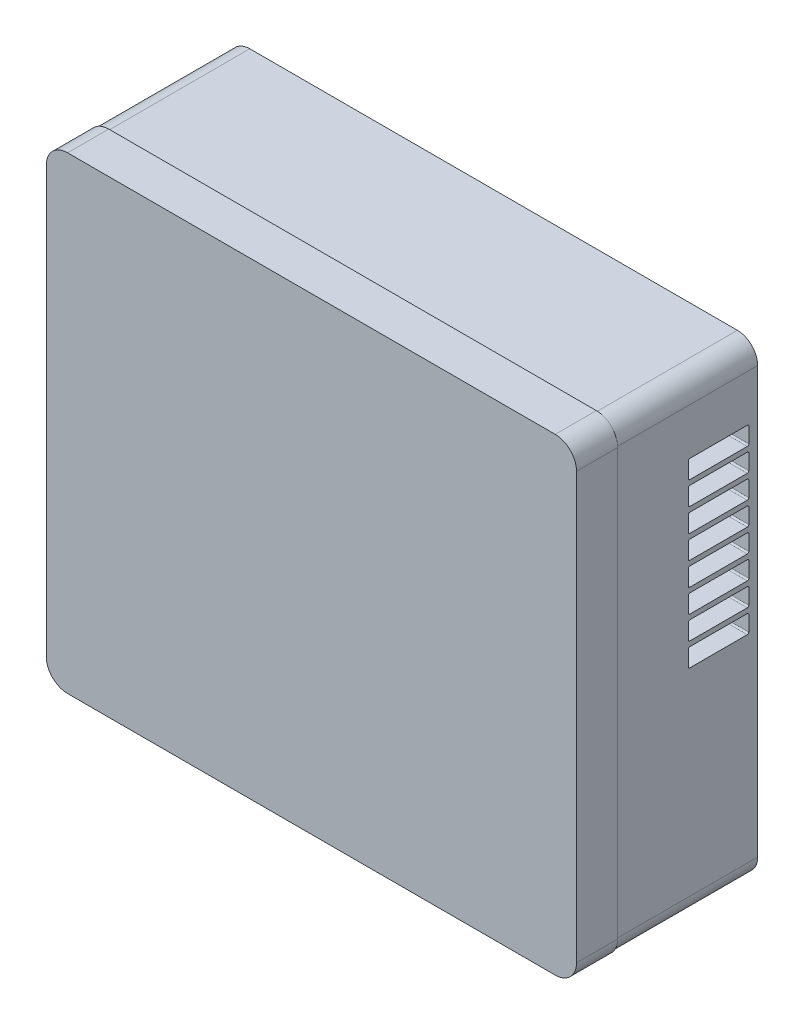
SolidWorks part; units mm, degrees
ref_plane "Front Plane" through (0, 0, 0) normal (0, 0, 1) x (1, 0, 0)
ref_plane "Top Plane" through (0, 0, 0) normal (0, 1, 0) x (1, 0, 0)
ref_plane "Right Plane" through (0, 0, 0) normal (1, 0, 0) x (0, 0, -1)
sketch "Sketch1" plane through (0, 0, 0) normal (0, 0, 1) x (1, 0, 0)
  line L4 (-86.3, 47.45) -> (-86.3, -38.45)
  line L5 (-84, -40.75) -> (14.4, -40.75)
  line L6 (16.7, -38.45) -> (16.7, 47.45)
  line L7 (14.4, 49.75) -> (-84, 49.75)
  line L8 (-86.3, 47.45) -> (-86.3, -38.45)
  line L9 (-84, -40.75) -> (14.4, -40.75)
  line L10 (16.7, -38.45) -> (16.7, 47.45)
  line L11 (14.4, 49.75) -> (-84, 49.75)
  arc A4 (-86.3, -38.45) -> (-84, -40.75) centre (-84, -38.45) ccw
  arc A5 (14.4, -40.75) -> (16.7, -38.45) centre (14.4, -38.45) ccw
  arc A6 (16.7, 47.45) -> (14.4, 49.75) centre (14.4, 47.45) ccw
  arc A7 (-84, 49.75) -> (-86.3, 47.45) centre (-84, 47.45) ccw
  arc A8 (-86.3, -38.45) -> (-84, -40.75) centre (-84, -38.45) ccw
  arc A9 (14.4, -40.75) -> (16.7, -38.45) centre (14.4, -38.45) ccw
  arc A10 (16.7, 47.45) -> (14.4, 49.75) centre (14.4, 47.45) ccw
  arc A11 (-84, 49.75) -> (-86.3, 47.45) centre (-84, 47.45) ccw
  dimension "D1" = 0
sketch "Sketch2" plane through (0, 0, 0) normal (0, 0, 1) x (1, 0, 0)
  line L4 (-86.3, 47.45) -> (-86.3, -38.45)
  line L5 (-84, -40.75) -> (14.4, -40.75)
  line L6 (16.7, -38.45) -> (16.7, 47.45)
  line L7 (14.4, 49.75) -> (-84, 49.75)
  line L8 (-86.3, 47.45) -> (-86.3, -38.45)
  line L9 (-84, -40.75) -> (14.4, -40.75)
  line L10 (16.7, -38.45) -> (16.7, 47.45)
  line L11 (14.4, 49.75) -> (-84, 49.75)
  arc A4 (-86.3, -38.45) -> (-84, -40.75) centre (-84, -38.45) ccw
  arc A5 (14.4, -40.75) -> (16.7, -38.45) centre (14.4, -38.45) ccw
  arc A6 (16.7, 47.45) -> (14.4, 49.75) centre (14.4, 47.45) ccw
  arc A7 (-84, 49.75) -> (-86.3, 47.45) centre (-84, 47.45) ccw
  arc A8 (-86.3, -38.45) -> (-84, -40.75) centre (-84, -38.45) ccw
  arc A9 (14.4, -40.75) -> (16.7, -38.45) centre (14.4, -38.45) ccw
  arc A10 (16.7, 47.45) -> (14.4, 49.75) centre (14.4, 47.45) ccw
  arc A11 (-84, 49.75) -> (-86.3, 47.45) centre (-84, 47.45) ccw
  dimension "D1" = 0
extrude "Boss-Extrude1" add sketch "Sketch2" along normal blind 2
sketch "Sketch3" plane through (0, 0, 2) normal (0, 0, 1) x (1, 0, 0)
  line L8 (-88.3, 47.45) -> (-88.3, -38.45)
  line L9 (-84, -42.75) -> (14.4, -42.75)
  line L10 (18.7, -38.45) -> (18.7, 47.45)
  line L11 (14.4, 51.75) -> (-84, 51.75)
  line L12 (-88.3, 47.45) -> (-88.3, -38.45)
  line L13 (-84, -42.75) -> (14.4, -42.75)
  line L14 (18.7, -38.45) -> (18.7, 47.45)
  line L15 (14.4, 51.75) -> (-84, 51.75)
  arc A8 (-84, 51.75) -> (-88.3, 47.45) centre (-84, 47.45) ccw
  arc A9 (-88.3, -38.45) -> (-84, -42.75) centre (-84, -38.45) ccw
  arc A10 (14.4, -42.75) -> (18.7, -38.45) centre (14.4, -38.45) ccw
  arc A11 (18.7, 47.45) -> (14.4, 51.75) centre (14.4, 47.45) ccw
  arc A12 (-84, 51.75) -> (-88.3, 47.45) centre (-84, 47.45) ccw
  arc A13 (-88.3, -38.45) -> (-84, -42.75) centre (-84, -38.45) ccw
  arc A14 (14.4, -42.75) -> (18.7, -38.45) centre (14.4, -38.45) ccw
  arc A15 (18.7, 47.45) -> (14.4, 51.75) centre (14.4, 47.45) ccw
  dimension "D1" = 2
extrude "Boss-Extrude3" add sketch "Sketch3" against normal blind 8.3
sketch "Sketch4" plane through (0, 0, -34.766) normal (0, 0, -1) x (-1, 0, 0)
  line L4 (61.7, 0.56) -> (61.7, 38.96)
  line L5 (61.7, 38.96) -> (3.9, 38.96)
  line L6 (3.9, 38.96) -> (3.9, 0.56)
  line L7 (3.9, 0.56) -> (61.7, 0.56)
  line L8 (61.7, 0.56) -> (61.7, 38.96)
  line L9 (61.7, 38.96) -> (3.9, 38.96)
  line L10 (3.9, 38.96) -> (3.9, 0.56)
  line L11 (3.9, 0.56) -> (61.7, 0.56)
  line L12 (-14.4, -40.55) -> (84, -40.55)
  line L13 (86.1, -38.45) -> (86.1, 47.45)
  line L14 (84, 49.55) -> (-14.4, 49.55)
  line L15 (-16.5, 47.45) -> (-16.5, -38.45)
  line L16 (-14.4, -40.55) -> (84, -40.55)
  line L17 (86.1, -38.45) -> (86.1, 47.45)
  line L18 (84, 49.55) -> (-14.4, 49.55)
  line L19 (-16.5, 47.45) -> (-16.5, -38.45)
  arc A4 (84, -40.55) -> (86.1, -38.45) centre (84, -38.45) ccw
  arc A5 (86.1, 47.45) -> (84, 49.55) centre (84, 47.45) ccw
  arc A6 (-14.4, 49.55) -> (-16.5, 47.45) centre (-14.4, 47.45) ccw
  arc A7 (-16.5, -38.45) -> (-14.4, -40.55) centre (-14.4, -38.45) ccw
  arc A8 (84, -40.55) -> (86.1, -38.45) centre (84, -38.45) ccw
  arc A9 (86.1, 47.45) -> (84, 49.55) centre (84, 47.45) ccw
  arc A10 (-14.4, 49.55) -> (-16.5, 47.45) centre (-14.4, 47.45) ccw
  arc A11 (-16.5, -38.45) -> (-14.4, -40.55) centre (-14.4, -38.45) ccw
  dimension "D1" = 0
  dimension "D2" = 0
extrude "Boss-Extrude5" add sketch "Sketch4" against normal blind 2 separate body
sketch "Sketch6" plane through (0, 0, -34.766) normal (0, 0, -1) x (-1, 0, 0)
  line L12 (-14.4, -42.55) -> (84, -42.55)
  line L13 (88.1, -38.45) -> (88.1, 47.45)
  line L14 (84, 51.55) -> (-14.4, 51.55)
  line L15 (-18.5, 47.45) -> (-18.5, -38.45)
  line L16 (-14.4, -42.55) -> (84, -42.55)
  line L17 (88.1, -38.45) -> (88.1, 47.45)
  line L18 (84, 51.55) -> (-14.4, 51.55)
  line L19 (-18.5, 47.45) -> (-18.5, -38.45)
  arc A12 (84, -42.55) -> (88.1, -38.45) centre (84, -38.45) ccw
  arc A13 (88.1, 47.45) -> (84, 51.55) centre (84, 47.45) ccw
  arc A14 (-14.4, 51.55) -> (-18.5, 47.45) centre (-14.4, 47.45) ccw
  arc A15 (-18.5, -38.45) -> (-14.4, -42.55) centre (-14.4, -38.45) ccw
  arc A16 (84, -42.55) -> (88.1, -38.45) centre (84, -38.45) ccw
  arc A17 (88.1, 47.45) -> (84, 51.55) centre (84, 47.45) ccw
  arc A18 (-14.4, 51.55) -> (-18.5, 47.45) centre (-14.4, 47.45) ccw
  arc A19 (-18.5, -38.45) -> (-14.4, -42.55) centre (-14.4, -38.45) ccw
  dimension "D1" = 2
extrude "Boss-Extrude6" add sketch "Sketch6" against normal up to surface (28.466 mm away) up to face at (-34.8, 4.5, -6.3)
sketch "Sketch7" plane through (0, 0, -34.766) normal (0, 0, -1) x (-1, 0, 0)
  line L4 (61.7, 0.56) -> (61.7, 38.96)
  line L5 (61.7, 38.96) -> (3.9, 38.96)
  line L6 (3.9, 38.96) -> (3.9, 0.56)
  line L7 (3.9, 0.56) -> (61.7, 0.56)
  line L8 (61.7, 0.56) -> (61.7, 38.96)
  line L9 (61.7, 38.96) -> (3.9, 38.96)
  line L10 (3.9, 38.96) -> (3.9, 0.56)
  line L11 (3.9, 0.56) -> (61.7, 0.56)
  dimension "D1" = 0
extrude "Cut-Extrude1" cut sketch "Sketch7" against normal blind 2
sketch "Sketch8" plane through (0, -42.55, 0) normal (0, -1, 0) x (1, 0, 0)
  line L0 (-68.12, -20.12) -> (-68.12, -6.47) construction
  line L1 (-68.12, -20.12) -> (-68.12, -6.47)
  line L2 (-55.38, -20.12) -> (-55.38, -6.47) construction
  line L3 (-55.38, -20.12) -> (-55.38, -6.47)
  line L4 (13.85, -17.47) -> (13.85, -6.47)
  line L5 (13.85, -6.47) -> (4.55, -6.47)
  line L6 (4.55, -6.47) -> (4.55, -17.47)
  line L7 (4.55, -17.47) -> (13.85, -17.47)
  line L8 (13.85, -17.47) -> (13.85, -6.47)
  line L9 (13.85, -6.47) -> (4.55, -6.47)
  line L10 (4.55, -6.47) -> (4.55, -17.47)
  line L11 (4.55, -17.47) -> (13.85, -17.47)
  line L12 (1.288, -13.3562) -> (1.288, -6.5462)
  line L13 (1.288, -6.5462) -> (-16.408, -6.5462)
  line L14 (-16.408, -6.5462) -> (-16.408, -13.3562)
  line L15 (-16.408, -13.3562) -> (1.288, -13.3562)
  line L16 (1.288, -13.3562) -> (1.288, -6.5462)
  line L17 (1.288, -6.5462) -> (-16.408, -6.5462)
  line L18 (-16.408, -6.5462) -> (-16.408, -13.3562)
  line L19 (-16.408, -13.3562) -> (1.288, -13.3562)
  line L20 (-20.375, -23.3862) -> (-20.375, -6.5462)
  line L21 (-20.375, -6.5462) -> (-34.425, -6.5462)
  line L22 (-34.425, -6.5462) -> (-34.425, -23.3862)
  line L23 (-34.425, -23.3862) -> (-20.375, -23.3862)
  line L24 (-20.375, -23.3862) -> (-20.375, -6.5462)
  line L25 (-20.375, -6.5462) -> (-34.425, -6.5462)
  line L26 (-34.425, -6.5462) -> (-34.425, -23.3862)
  line L27 (-34.425, -23.3862) -> (-20.375, -23.3862)
  line L28 (-37.375, -23.3862) -> (-37.375, -6.5462)
  line L29 (-37.375, -6.5462) -> (-51.425, -6.5462)
  line L30 (-51.425, -6.5462) -> (-51.425, -23.3862)
  line L31 (-51.425, -23.3862) -> (-37.375, -23.3862)
  line L32 (-37.375, -23.3862) -> (-37.375, -6.5462)
  line L33 (-37.375, -6.5462) -> (-51.425, -6.5462)
  line L34 (-51.425, -6.5462) -> (-51.425, -23.3862)
  line L35 (-51.425, -23.3862) -> (-37.375, -23.3862)
  line L36 (-57.38, -20.12) -> (-57.38, -6.47)
  line L37 (-57.38, -6.47) -> (-66.12, -6.47)
  line L38 (-66.12, -6.47) -> (-66.12, -20.12)
  line L39 (-66.12, -20.12) -> (-57.38, -20.12)
  line L40 (-57.38, -20.12) -> (-57.38, -6.47)
  line L41 (-57.38, -6.47) -> (-66.12, -6.47)
  line L42 (-66.12, -6.47) -> (-66.12, -20.12)
  line L43 (-66.12, -20.12) -> (-57.38, -20.12)
  line L44 (-72.33, -9.9762) -> (-72.33, -6.5462)
  line L45 (-72.33, -6.5462) -> (-81.22, -6.5462)
  line L46 (-81.22, -6.5462) -> (-81.22, -9.9762)
  line L47 (-81.22, -9.9762) -> (-72.33, -9.9762)
  line L48 (-72.33, -9.9762) -> (-72.33, -6.5462)
  line L49 (-72.33, -6.5462) -> (-81.22, -6.5462)
  line L50 (-81.22, -6.5462) -> (-81.22, -9.9762)
  line L51 (-81.22, -9.9762) -> (-72.33, -9.9762)
  line L52 (-53.673, -6.47) -> (-53.673, -20.12) construction
  line L53 (-53.673, -6.47) -> (-53.673, -20.12)
  line L54 (-69.827, -20.12) -> (-69.827, -6.47) construction
  line L55 (-69.827, -20.12) -> (-69.827, -6.47)
  dimension "D1" = 0
  dimension "D2" = 0
  dimension "D3" = 0
  dimension "D4" = 0
  dimension "D5" = 0
  dimension "D6" = 0
sketch "Sketch9" plane through (0, -42.55, 0) normal (0, -1, 0) x (1, 0, 0)
  line L0 (-57.38, -20.12) -> (-57.38, -6.47) construction
  line L1 (-57.38, -20.12) -> (-57.38, -6.47)
  line L2 (-68.12, -20.12) -> (-68.12, -6.47) construction
  line L3 (-68.12, -20.12) -> (-68.12, -6.47)
  line L4 (13.85, -17.47) -> (13.85, -6.47)
  line L5 (13.85, -6.47) -> (4.55, -6.47)
  line L6 (4.55, -6.47) -> (4.55, -17.47)
  line L7 (4.55, -17.47) -> (13.85, -17.47)
  line L8 (13.85, -17.47) -> (13.85, -6.47)
  line L9 (13.85, -6.47) -> (4.55, -6.47)
  line L10 (4.55, -6.47) -> (4.55, -17.47)
  line L11 (4.55, -17.47) -> (13.85, -17.47)
  line L12 (1.288, -13.3562) -> (1.288, -6.5462)
  line L13 (1.288, -6.5462) -> (-16.408, -6.5462)
  line L14 (-16.408, -6.5462) -> (-16.408, -13.3562)
  line L15 (-16.408, -13.3562) -> (1.288, -13.3562)
  line L16 (1.288, -13.3562) -> (1.288, -6.5462)
  line L17 (1.288, -6.5462) -> (-16.408, -6.5462)
  line L18 (-16.408, -6.5462) -> (-16.408, -13.3562)
  line L19 (-16.408, -13.3562) -> (1.288, -13.3562)
  line L20 (-20.375, -23.3862) -> (-20.375, -6.5462)
  line L21 (-20.375, -6.5462) -> (-34.425, -6.5462)
  line L22 (-34.425, -6.5462) -> (-34.425, -23.3862)
  line L23 (-34.425, -23.3862) -> (-20.375, -23.3862)
  line L24 (-20.375, -23.3862) -> (-20.375, -6.5462)
  line L25 (-20.375, -6.5462) -> (-34.425, -6.5462)
  line L26 (-34.425, -6.5462) -> (-34.425, -23.3862)
  line L27 (-34.425, -23.3862) -> (-20.375, -23.3862)
  line L28 (-37.375, -23.3862) -> (-37.375, -6.5462)
  line L29 (-37.375, -6.5462) -> (-51.425, -6.5462)
  line L30 (-51.425, -6.5462) -> (-51.425, -23.3862)
  line L31 (-51.425, -23.3862) -> (-37.375, -23.3862)
  line L32 (-37.375, -23.3862) -> (-37.375, -6.5462)
  line L33 (-37.375, -6.5462) -> (-51.425, -6.5462)
  line L34 (-51.425, -6.5462) -> (-51.425, -23.3862)
  line L35 (-51.425, -23.3862) -> (-37.375, -23.3862)
  line L36 (-53.673, -20.12) -> (-53.673, -6.47)
  line L37 (-53.673, -6.47) -> (-55.38, -6.47)
  line L38 (-55.38, -6.47) -> (-55.38, -20.12)
  line L39 (-55.38, -20.12) -> (-53.673, -20.12)
  line L40 (-53.673, -20.12) -> (-53.673, -6.47)
  line L41 (-53.673, -6.47) -> (-55.38, -6.47)
  line L42 (-55.38, -6.47) -> (-55.38, -20.12)
  line L43 (-55.38, -20.12) -> (-53.673, -20.12)
  line L44 (-69.827, -6.47) -> (-69.827, -20.12) construction
  line L45 (-69.827, -6.47) -> (-69.827, -20.12)
  line L46 (-57.38, -20.12) -> (-57.38, -6.47)
  line L47 (-57.38, -6.47) -> (-66.12, -6.47)
  line L48 (-66.12, -6.47) -> (-66.12, -20.12)
  line L49 (-66.12, -20.12) -> (-57.38, -20.12)
  line L50 (-57.38, -20.12) -> (-57.38, -6.47)
  line L51 (-57.38, -6.47) -> (-66.12, -6.47)
  line L52 (-66.12, -6.47) -> (-66.12, -20.12)
  line L53 (-66.12, -20.12) -> (-57.38, -20.12)
  line L58 (-72.33, -9.9762) -> (-72.33, -6.5462)
  line L59 (-72.33, -6.5462) -> (-81.22, -6.5462)
  line L60 (-81.22, -6.5462) -> (-81.22, -9.9762)
  line L61 (-81.22, -9.9762) -> (-72.33, -9.9762)
  line L62 (-72.33, -9.9762) -> (-72.33, -6.5462)
  line L63 (-72.33, -6.5462) -> (-81.22, -6.5462)
  line L64 (-81.22, -6.5462) -> (-81.22, -9.9762)
  line L65 (-81.22, -9.9762) -> (-72.33, -9.9762)
  line L66 (-55.38, -20.12) -> (-55.38, -6.47)
  line L67 (-55.38, -6.47) -> (-57.38, -6.47)
  line L68 (-57.38, -6.47) -> (-57.38, -20.12)
  line L69 (-57.38, -20.12) -> (-55.38, -20.12)
  line L70 (-55.38, -20.12) -> (-55.38, -6.47)
  line L71 (-55.38, -6.47) -> (-57.38, -6.47)
  line L72 (-57.38, -6.47) -> (-57.38, -20.12)
  line L73 (-57.38, -20.12) -> (-55.38, -20.12)
  line L74 (-66.12, -20.12) -> (-66.12, -6.47)
  line L75 (-66.12, -6.47) -> (-68.12, -6.47)
  line L76 (-68.12, -6.47) -> (-68.12, -20.12)
  line L77 (-68.12, -20.12) -> (-66.12, -20.12)
  line L78 (-66.12, -20.12) -> (-66.12, -6.47)
  line L79 (-66.12, -6.47) -> (-68.12, -6.47)
  line L80 (-68.12, -6.47) -> (-68.12, -20.12)
  line L81 (-68.12, -20.12) -> (-66.12, -20.12)
  line L82 (-68.12, -20.12) -> (-68.12, -6.47)
  line L83 (-68.12, -6.47) -> (-69.827, -6.47)
  line L84 (-69.827, -6.47) -> (-69.827, -20.12)
  line L85 (-69.827, -20.12) -> (-68.12, -20.12)
  line L86 (-68.12, -20.12) -> (-68.12, -6.47)
  line L87 (-68.12, -6.47) -> (-69.827, -6.47)
  line L88 (-69.827, -6.47) -> (-69.827, -20.12)
  line L89 (-69.827, -20.12) -> (-68.12, -20.12)
  dimension "D1" = 0
  dimension "D2" = 0
  dimension "D3" = 0
  dimension "D4" = 0
  dimension "D5" = 0
  dimension "D6" = 0
  dimension "D7" = 0
  dimension "D8" = 0
  dimension "D9" = 0
  dimension "D10" = 0
extrude "Cut-Extrude2" cut sketch "Sketch9" against normal blind 2 contours L10 L11 L8 L9 | L18 L19 L16 L17 | L26 L27 L24 L25 | L34 L35 L32 L33 | L1 L73 L42 L71 | L52 L53 L1 L51 | L3 L81 L52 L79 | L45 L89 L3 L87 | L64 L65 L62 L63
sketch "Sketch13" plane through (18.5, 0, 0) normal (1, 0, 0) x (0, 0, -1)
  line L0 (32.966, 1.76) -> (32.966, 4.86) construction
  line L1 (32.666, 1.46) -> (21.066, 1.46) construction
  line L2 (20.766, 4.86) -> (20.766, 1.76) construction
  line L3 (32.666, 5.16) -> (21.066, 5.16) construction
  line L4 (32.966, 1.76) -> (32.966, 4.86)
  line L5 (32.666, 1.46) -> (21.066, 1.46)
  line L6 (20.766, 4.86) -> (20.766, 1.76)
  line L7 (32.666, 5.16) -> (21.066, 5.16)
  arc A0 (32.966, 4.86) -> (32.666, 5.16) centre (32.666, 4.86) ccw construction
  arc A1 (32.666, 1.46) -> (32.966, 1.76) centre (32.666, 1.76) ccw construction
  arc A2 (20.766, 1.76) -> (21.066, 1.46) centre (21.066, 1.76) ccw construction
  arc A3 (21.066, 5.16) -> (20.766, 4.86) centre (21.066, 4.86) ccw construction
  arc A4 (32.966, 4.86) -> (32.666, 5.16) centre (32.666, 4.86) ccw
  arc A5 (32.666, 1.46) -> (32.966, 1.76) centre (32.666, 1.76) ccw
  arc A6 (20.766, 1.76) -> (21.066, 1.46) centre (21.066, 1.76) ccw
  arc A7 (21.066, 5.16) -> (20.766, 4.86) centre (21.066, 4.86) ccw
extrude "Cut-Extrude3" cut sketch "Sketch13" against normal blind 2
sketch "Sketch14" plane through (-3.9, 0, 0) normal (1, 0, 0) x (0, 0, -1)
  line L0 (32.966, 34.66) -> (32.966, 37.76) construction
  line L1 (32.666, 38.06) -> (21.066, 38.06) construction
  line L2 (21.066, 34.36) -> (32.666, 34.36) construction
  line L3 (20.766, 37.76) -> (20.766, 34.66) construction
  line L4 (20.766, 33.06) -> (20.766, 29.96) construction
  line L5 (32.666, 33.36) -> (21.066, 33.36) construction
  line L6 (21.066, 29.66) -> (32.666, 29.66) construction
  line L7 (32.966, 29.96) -> (32.966, 33.06) construction
  line L8 (32.666, 28.66) -> (21.066, 28.66) construction
  line L9 (20.766, 28.36) -> (20.766, 25.26) construction
  line L10 (32.666, 24.96) -> (21.066, 24.96) construction
  line L11 (32.966, 25.26) -> (32.966, 28.36) construction
  line L12 (32.666, 23.96) -> (21.066, 23.96) construction
  line L13 (32.966, 20.56) -> (32.966, 23.66) construction
  line L14 (32.666, 20.26) -> (21.066, 20.26) construction
  line L15 (20.766, 23.66) -> (20.766, 20.56) construction
  line L16 (32.666, 19.26) -> (21.066, 19.26) construction
  line L17 (32.966, 15.86) -> (32.966, 18.96) construction
  line L18 (32.666, 15.56) -> (21.066, 15.56) construction
  line L19 (20.766, 18.96) -> (20.766, 15.86) construction
  line L20 (32.666, 14.56) -> (21.066, 14.56) construction
  line L21 (32.966, 11.16) -> (32.966, 14.26) construction
  line L22 (32.666, 10.86) -> (21.066, 10.86) construction
  line L23 (20.766, 14.26) -> (20.766, 11.16) construction
  line L24 (20.766, 9.56) -> (20.766, 6.46) construction
  line L25 (32.666, 9.86) -> (21.066, 9.86) construction
  line L26 (32.966, 6.46) -> (32.966, 9.56) construction
  line L27 (32.666, 6.16) -> (21.066, 6.16) construction
  line L28 (32.966, 34.66) -> (32.966, 37.76)
  line L29 (32.666, 38.06) -> (21.066, 38.06)
  line L30 (21.066, 34.36) -> (32.666, 34.36)
  line L31 (20.766, 37.76) -> (20.766, 34.66)
  line L32 (20.766, 33.06) -> (20.766, 29.96)
  line L33 (32.666, 33.36) -> (21.066, 33.36)
  line L34 (21.066, 29.66) -> (32.666, 29.66)
  line L35 (32.966, 29.96) -> (32.966, 33.06)
  line L36 (32.666, 28.66) -> (21.066, 28.66)
  line L37 (20.766, 28.36) -> (20.766, 25.26)
  line L38 (32.666, 24.96) -> (21.066, 24.96)
  line L39 (32.966, 25.26) -> (32.966, 28.36)
  line L40 (32.666, 23.96) -> (21.066, 23.96)
  line L41 (32.966, 20.56) -> (32.966, 23.66)
  line L42 (32.666, 20.26) -> (21.066, 20.26)
  line L43 (20.766, 23.66) -> (20.766, 20.56)
  line L44 (32.666, 19.26) -> (21.066, 19.26)
  line L45 (32.966, 15.86) -> (32.966, 18.96)
  line L46 (32.666, 15.56) -> (21.066, 15.56)
  line L47 (20.766, 18.96) -> (20.766, 15.86)
  line L48 (32.666, 14.56) -> (21.066, 14.56)
  line L49 (32.966, 11.16) -> (32.966, 14.26)
  line L50 (32.666, 10.86) -> (21.066, 10.86)
  line L51 (20.766, 14.26) -> (20.766, 11.16)
  line L52 (20.766, 9.56) -> (20.766, 6.46)
  line L53 (32.666, 9.86) -> (21.066, 9.86)
  line L54 (32.966, 6.46) -> (32.966, 9.56)
  line L55 (32.666, 6.16) -> (21.066, 6.16)
  arc A0 (32.666, 34.36) -> (32.966, 34.66) centre (32.666, 34.66) ccw construction
  arc A1 (32.966, 37.76) -> (32.666, 38.06) centre (32.666, 37.76) ccw construction
  arc A2 (20.766, 34.66) -> (21.066, 34.36) centre (21.066, 34.66) ccw construction
  arc A3 (21.066, 38.06) -> (20.766, 37.76) centre (21.066, 37.76) ccw construction
  arc A4 (20.766, 29.96) -> (21.066, 29.66) centre (21.066, 29.96) ccw construction
  arc A5 (21.066, 33.36) -> (20.766, 33.06) centre (21.066, 33.06) ccw construction
  arc A6 (32.966, 33.06) -> (32.666, 33.36) centre (32.666, 33.06) ccw construction
  arc A7 (32.666, 29.66) -> (32.966, 29.96) centre (32.666, 29.96) ccw construction
  arc A8 (32.966, 28.36) -> (32.666, 28.66) centre (32.666, 28.36) ccw construction
  arc A9 (21.066, 28.66) -> (20.766, 28.36) centre (21.066, 28.36) ccw construction
  arc A10 (20.766, 25.26) -> (21.066, 24.96) centre (21.066, 25.26) ccw construction
  arc A11 (32.666, 24.96) -> (32.966, 25.26) centre (32.666, 25.26) ccw construction
  arc A12 (32.966, 23.66) -> (32.666, 23.96) centre (32.666, 23.66) ccw construction
  arc A13 (32.666, 20.26) -> (32.966, 20.56) centre (32.666, 20.56) ccw construction
  arc A14 (20.766, 20.56) -> (21.066, 20.26) centre (21.066, 20.56) ccw construction
  arc A15 (21.066, 23.96) -> (20.766, 23.66) centre (21.066, 23.66) ccw construction
  arc A16 (21.066, 19.26) -> (20.766, 18.96) centre (21.066, 18.96) ccw construction
  arc A17 (32.966, 18.96) -> (32.666, 19.26) centre (32.666, 18.96) ccw construction
  arc A18 (32.666, 15.56) -> (32.966, 15.86) centre (32.666, 15.86) ccw construction
  arc A19 (20.766, 15.86) -> (21.066, 15.56) centre (21.066, 15.86) ccw construction
  arc A20 (32.966, 14.26) -> (32.666, 14.56) centre (32.666, 14.26) ccw construction
  arc A21 (32.666, 10.86) -> (32.966, 11.16) centre (32.666, 11.16) ccw construction
  arc A22 (20.766, 11.16) -> (21.066, 10.86) centre (21.066, 11.16) ccw construction
  arc A23 (21.066, 14.56) -> (20.766, 14.26) centre (21.066, 14.26) ccw construction
  arc A24 (20.766, 6.46) -> (21.066, 6.16) centre (21.066, 6.46) ccw construction
  arc A25 (21.066, 9.86) -> (20.766, 9.56) centre (21.066, 9.56) ccw construction
  arc A26 (32.966, 9.56) -> (32.666, 9.86) centre (32.666, 9.56) ccw construction
  arc A27 (32.666, 6.16) -> (32.966, 6.46) centre (32.666, 6.46) ccw construction
  arc A28 (32.666, 34.36) -> (32.966, 34.66) centre (32.666, 34.66) ccw
  arc A29 (32.966, 37.76) -> (32.666, 38.06) centre (32.666, 37.76) ccw
  arc A30 (20.766, 34.66) -> (21.066, 34.36) centre (21.066, 34.66) ccw
  arc A31 (21.066, 38.06) -> (20.766, 37.76) centre (21.066, 37.76) ccw
  arc A32 (20.766, 29.96) -> (21.066, 29.66) centre (21.066, 29.96) ccw
  arc A33 (21.066, 33.36) -> (20.766, 33.06) centre (21.066, 33.06) ccw
  arc A34 (32.966, 33.06) -> (32.666, 33.36) centre (32.666, 33.06) ccw
  arc A35 (32.666, 29.66) -> (32.966, 29.96) centre (32.666, 29.96) ccw
  arc A36 (32.966, 28.36) -> (32.666, 28.66) centre (32.666, 28.36) ccw
  arc A37 (21.066, 28.66) -> (20.766, 28.36) centre (21.066, 28.36) ccw
  arc A38 (20.766, 25.26) -> (21.066, 24.96) centre (21.066, 25.26) ccw
  arc A39 (32.666, 24.96) -> (32.966, 25.26) centre (32.666, 25.26) ccw
  arc A40 (32.966, 23.66) -> (32.666, 23.96) centre (32.666, 23.66) ccw
  arc A41 (32.666, 20.26) -> (32.966, 20.56) centre (32.666, 20.56) ccw
  arc A42 (20.766, 20.56) -> (21.066, 20.26) centre (21.066, 20.56) ccw
  arc A43 (21.066, 23.96) -> (20.766, 23.66) centre (21.066, 23.66) ccw
  arc A44 (21.066, 19.26) -> (20.766, 18.96) centre (21.066, 18.96) ccw
  arc A45 (32.966, 18.96) -> (32.666, 19.26) centre (32.666, 18.96) ccw
  arc A46 (32.666, 15.56) -> (32.966, 15.86) centre (32.666, 15.86) ccw
  arc A47 (20.766, 15.86) -> (21.066, 15.56) centre (21.066, 15.86) ccw
  arc A48 (32.966, 14.26) -> (32.666, 14.56) centre (32.666, 14.26) ccw
  arc A49 (32.666, 10.86) -> (32.966, 11.16) centre (32.666, 11.16) ccw
  arc A50 (20.766, 11.16) -> (21.066, 10.86) centre (21.066, 11.16) ccw
  arc A51 (21.066, 14.56) -> (20.766, 14.26) centre (21.066, 14.26) ccw
  arc A52 (20.766, 6.46) -> (21.066, 6.16) centre (21.066, 6.46) ccw
  arc A53 (21.066, 9.86) -> (20.766, 9.56) centre (21.066, 9.56) ccw
  arc A54 (32.966, 9.56) -> (32.666, 9.86) centre (32.666, 9.56) ccw
  arc A55 (32.666, 6.16) -> (32.966, 6.46) centre (32.666, 6.46) ccw
extrude "Cut-Extrude4" cut sketch "Sketch14" against normal blind 2
sketch "Sketch15" plane through (18.5, 0, 0) normal (1, 0, 0) x (0, 0, -1)
  line L0 (20.766, 9.56) -> (20.766, 6.46) construction
  line L1 (32.666, 6.16) -> (21.066, 6.16) construction
  line L2 (32.966, 6.46) -> (32.966, 9.56) construction
  line L3 (32.666, 9.86) -> (21.066, 9.86) construction
  line L4 (20.766, 9.56) -> (20.766, 6.46)
  line L5 (32.666, 6.16) -> (21.066, 6.16)
  line L6 (32.966, 6.46) -> (32.966, 9.56)
  line L7 (32.666, 9.86) -> (21.066, 9.86)
  arc A0 (21.066, 9.86) -> (20.766, 9.56) centre (21.066, 9.56) ccw construction
  arc A1 (20.766, 6.46) -> (21.066, 6.16) centre (21.066, 6.46) ccw construction
  arc A2 (32.666, 6.16) -> (32.966, 6.46) centre (32.666, 6.46) ccw construction
  arc A3 (32.966, 9.56) -> (32.666, 9.86) centre (32.666, 9.56) ccw construction
  arc A4 (21.066, 9.86) -> (20.766, 9.56) centre (21.066, 9.56) ccw
  arc A5 (20.766, 6.46) -> (21.066, 6.16) centre (21.066, 6.46) ccw
  arc A6 (32.666, 6.16) -> (32.966, 6.46) centre (32.666, 6.46) ccw
  arc A7 (32.966, 9.56) -> (32.666, 9.86) centre (32.666, 9.56) ccw
extrude "Cut-Extrude5" cut sketch "Sketch15" against normal blind 2
sketch "Sketch16" plane through (18.5, 0, 0) normal (1, 0, 0) x (0, 0, -1)
  line L0 (32.966, 11.16) -> (32.966, 14.26) construction
  line L1 (32.666, 10.86) -> (21.066, 10.86) construction
  line L2 (32.666, 14.56) -> (21.066, 14.56) construction
  line L3 (20.766, 14.26) -> (20.766, 11.16) construction
  line L12 (32.966, 11.16) -> (32.966, 14.26)
  line L13 (32.666, 10.86) -> (21.066, 10.86)
  line L14 (32.666, 14.56) -> (21.066, 14.56)
  line L15 (20.766, 14.26) -> (20.766, 11.16)
  line L16 (20.766, 37.76) -> (20.766, 34.66) construction
  line L17 (32.666, 38.06) -> (21.066, 38.06) construction
  line L18 (32.966, 34.66) -> (32.966, 37.76) construction
  line L19 (21.066, 34.36) -> (32.666, 34.36) construction
  line L20 (20.766, 9.56) -> (20.766, 6.46)
  line L21 (21.066, 6.16) -> (32.666, 6.16)
  line L22 (32.966, 6.46) -> (32.966, 9.56)
  line L23 (32.666, 9.86) -> (21.066, 9.86)
  line L24 (20.766, 9.56) -> (20.766, 6.46)
  line L25 (21.066, 6.16) -> (32.666, 6.16)
  line L26 (32.966, 6.46) -> (32.966, 9.56)
  line L27 (32.666, 9.86) -> (21.066, 9.86)
  line L28 (20.166, 6.46) -> (17.966, 6.46)
  line L29 (17.966, 6.46) -> (17.966, 0.26)
  line L30 (17.966, 0.26) -> (34.466, 0.26)
  line L31 (34.766, 0.56) -> (34.766, 38.96)
  line L32 (34.466, 39.26) -> (17.966, 39.26)
  line L33 (17.966, 39.26) -> (17.966, 37.08)
  line L34 (17.966, 37.08) -> (18.166, 37.08)
  line L35 (18.166, 37.08) -> (18.166, 30.98)
  line L36 (18.166, 30.98) -> (17.966, 30.98)
  line L37 (17.966, 30.98) -> (17.966, 17.535)
  line L38 (17.966, 17.535) -> (20.166, 17.535)
  line L39 (20.166, 17.535) -> (20.166, 6.46)
  line L46 (17.966, 37.08) -> (18.166, 37.08)
  line L48 (18.166, 30.98) -> (17.966, 30.98)
  line L52 (32.666, 5.16) -> (21.066, 5.16)
  line L53 (20.766, 4.86) -> (20.766, 1.76)
  line L54 (21.066, 1.46) -> (32.666, 1.46)
  line L55 (32.966, 1.76) -> (32.966, 4.86)
  line L56 (32.666, 5.16) -> (21.066, 5.16)
  line L57 (20.766, 4.86) -> (20.766, 1.76)
  line L58 (21.066, 1.46) -> (32.666, 1.46)
  line L59 (32.966, 1.76) -> (32.966, 4.86)
  line L61 (20.766, 33.06) -> (20.766, 29.96) construction
  line L62 (32.966, 29.96) -> (32.966, 33.06) construction
  line L63 (32.666, 33.36) -> (21.066, 33.36) construction
  line L64 (21.066, 29.66) -> (32.666, 29.66) construction
  line L65 (32.666, 24.96) -> (21.066, 24.96) construction
  line L66 (32.666, 28.66) -> (21.066, 28.66) construction
  line L67 (32.966, 25.26) -> (32.966, 28.36) construction
  line L68 (32.966, 20.56) -> (32.966, 23.66) construction
  line L69 (32.666, 23.96) -> (21.066, 23.96) construction
  line L70 (32.666, 20.26) -> (21.066, 20.26) construction
  line L71 (32.966, 15.86) -> (32.966, 18.96) construction
  line L72 (32.666, 15.56) -> (21.066, 15.56) construction
  line L73 (32.666, 19.26) -> (21.066, 19.26) construction
  line L74 (20.766, 37.76) -> (20.766, 34.66)
  line L75 (32.666, 38.06) -> (21.066, 38.06)
  line L76 (32.966, 34.66) -> (32.966, 37.76)
  line L77 (21.066, 34.36) -> (32.666, 34.36)
  line L78 (20.766, 25.26) -> (20.766, 28.36)
  line L79 (20.766, 33.06) -> (20.766, 29.96)
  line L80 (32.966, 29.96) -> (32.966, 33.06)
  line L81 (32.666, 33.36) -> (21.066, 33.36)
  line L82 (21.066, 29.66) -> (32.666, 29.66)
  line L83 (32.666, 24.96) -> (21.066, 24.96)
  line L84 (32.666, 28.66) -> (21.066, 28.66)
  line L85 (32.966, 25.26) -> (32.966, 28.36)
  line L86 (32.966, 20.56) -> (32.966, 23.66)
  line L87 (32.666, 23.96) -> (21.066, 23.96)
  line L88 (32.666, 20.26) -> (21.066, 20.26)
  line L89 (32.966, 15.86) -> (32.966, 18.96)
  line L90 (32.666, 15.56) -> (21.066, 15.56)
  line L91 (32.666, 19.26) -> (21.066, 19.26)
  line L92 (20.766, 20.56) -> (20.766, 23.66)
  line L93 (20.766, 15.86) -> (20.766, 18.96)
  arc A0 (32.666, 10.86) -> (32.966, 11.16) centre (32.666, 11.16) ccw construction
  arc A1 (32.966, 14.26) -> (32.666, 14.56) centre (32.666, 14.26) ccw construction
  arc A2 (20.766, 11.16) -> (21.066, 10.86) centre (21.066, 11.16) ccw construction
  arc A3 (21.066, 14.56) -> (20.766, 14.26) centre (21.066, 14.26) ccw construction
  arc A4 (32.666, 10.86) -> (32.966, 11.16) centre (32.666, 11.16) ccw
  arc A5 (32.966, 14.26) -> (32.666, 14.56) centre (32.666, 14.26) ccw
  arc A6 (20.766, 11.16) -> (21.066, 10.86) centre (21.066, 11.16) ccw
  arc A7 (21.066, 14.56) -> (20.766, 14.26) centre (21.066, 14.26) ccw
  arc A8 (20.766, 34.66) -> (21.066, 34.36) centre (21.066, 34.66) ccw construction
  arc A9 (21.066, 38.06) -> (20.766, 37.76) centre (21.066, 37.76) ccw construction
  arc A10 (34.466, 0.26) -> (34.766, 0.56) centre (34.466, 0.56) ccw
  arc A11 (34.766, 38.96) -> (34.466, 39.26) centre (34.466, 38.96) ccw
  arc A12 (34.466, 0.26) -> (34.766, 0.56) centre (34.466, 0.56) ccw
  arc A13 (34.766, 38.96) -> (34.466, 39.26) centre (34.466, 38.96) ccw
  arc A14 (32.966, 37.76) -> (32.666, 38.06) centre (32.666, 37.76) ccw construction
  arc A15 (32.666, 34.36) -> (32.966, 34.66) centre (32.666, 34.66) ccw construction
  arc A16 (21.066, 9.86) -> (20.766, 9.56) centre (21.066, 9.56) ccw
  arc A17 (20.766, 6.46) -> (21.066, 6.16) centre (21.066, 6.46) ccw
  arc A18 (32.666, 6.16) -> (32.966, 6.46) centre (32.666, 6.46) ccw
  arc A19 (32.966, 9.56) -> (32.666, 9.86) centre (32.666, 9.56) ccw
  arc A20 (21.066, 9.86) -> (20.766, 9.56) centre (21.066, 9.56) ccw
  arc A21 (20.766, 6.46) -> (21.066, 6.16) centre (21.066, 6.46) ccw
  arc A22 (32.666, 6.16) -> (32.966, 6.46) centre (32.666, 6.46) ccw
  arc A23 (32.966, 9.56) -> (32.666, 9.86) centre (32.666, 9.56) ccw
  arc A24 (32.966, 4.86) -> (32.666, 5.16) centre (32.666, 4.86) ccw
  arc A25 (21.066, 5.16) -> (20.766, 4.86) centre (21.066, 4.86) ccw
  arc A26 (20.766, 1.76) -> (21.066, 1.46) centre (21.066, 1.76) ccw
  arc A27 (32.666, 1.46) -> (32.966, 1.76) centre (32.666, 1.76) ccw
  arc A28 (32.966, 4.86) -> (32.666, 5.16) centre (32.666, 4.86) ccw
  arc A29 (21.066, 5.16) -> (20.766, 4.86) centre (21.066, 4.86) ccw
  arc A30 (20.766, 1.76) -> (21.066, 1.46) centre (21.066, 1.76) ccw
  arc A31 (32.666, 1.46) -> (32.966, 1.76) centre (32.666, 1.76) ccw
  arc A32 (20.766, 29.96) -> (21.066, 29.66) centre (21.066, 29.96) ccw construction
  arc A33 (21.066, 33.36) -> (20.766, 33.06) centre (21.066, 33.06) ccw construction
  arc A34 (32.966, 33.06) -> (32.666, 33.36) centre (32.666, 33.06) ccw construction
  arc A35 (32.666, 29.66) -> (32.966, 29.96) centre (32.666, 29.96) ccw construction
  arc A36 (21.066, 28.66) -> (20.766, 28.36) centre (21.066, 28.36) ccw construction
  arc A37 (20.766, 25.26) -> (21.066, 24.96) centre (21.066, 25.26) ccw construction
  arc A38 (32.966, 28.36) -> (32.666, 28.66) centre (32.666, 28.36) ccw construction
  arc A39 (32.666, 24.96) -> (32.966, 25.26) centre (32.666, 25.26) ccw construction
  arc A40 (32.966, 23.66) -> (32.666, 23.96) centre (32.666, 23.66) ccw construction
  arc A41 (32.666, 20.26) -> (32.966, 20.56) centre (32.666, 20.56) ccw construction
  arc A42 (21.066, 23.96) -> (20.766, 23.66) centre (21.066, 23.66) ccw construction
  arc A43 (20.766, 20.56) -> (21.066, 20.26) centre (21.066, 20.56) ccw construction
  arc A44 (20.766, 15.86) -> (21.066, 15.56) centre (21.066, 15.86) ccw construction
  arc A45 (21.066, 19.26) -> (20.766, 18.96) centre (21.066, 18.96) ccw construction
  arc A46 (32.666, 15.56) -> (32.966, 15.86) centre (32.666, 15.86) ccw construction
  arc A47 (32.966, 18.96) -> (32.666, 19.26) centre (32.666, 18.96) ccw construction
  arc A48 (20.766, 34.66) -> (21.066, 34.36) centre (21.066, 34.66) ccw
  arc A49 (21.066, 38.06) -> (20.766, 37.76) centre (21.066, 37.76) ccw
  arc A50 (32.966, 37.76) -> (32.666, 38.06) centre (32.666, 37.76) ccw
  arc A51 (32.666, 34.36) -> (32.966, 34.66) centre (32.666, 34.66) ccw
  arc A52 (20.766, 29.96) -> (21.066, 29.66) centre (21.066, 29.96) ccw
  arc A53 (21.066, 33.36) -> (20.766, 33.06) centre (21.066, 33.06) ccw
  arc A54 (32.966, 33.06) -> (32.666, 33.36) centre (32.666, 33.06) ccw
  arc A55 (32.666, 29.66) -> (32.966, 29.96) centre (32.666, 29.96) ccw
  arc A56 (21.066, 28.66) -> (20.766, 28.36) centre (21.066, 28.36) ccw
  arc A57 (20.766, 25.26) -> (21.066, 24.96) centre (21.066, 25.26) ccw
  arc A58 (32.966, 28.36) -> (32.666, 28.66) centre (32.666, 28.36) ccw
  arc A59 (32.666, 24.96) -> (32.966, 25.26) centre (32.666, 25.26) ccw
  arc A60 (32.966, 23.66) -> (32.666, 23.96) centre (32.666, 23.66) ccw
  arc A61 (32.666, 20.26) -> (32.966, 20.56) centre (32.666, 20.56) ccw
  arc A62 (21.066, 23.96) -> (20.766, 23.66) centre (21.066, 23.66) ccw
  arc A63 (20.766, 20.56) -> (21.066, 20.26) centre (21.066, 20.56) ccw
  arc A64 (20.766, 15.86) -> (21.066, 15.56) centre (21.066, 15.86) ccw
  arc A65 (21.066, 19.26) -> (20.766, 18.96) centre (21.066, 18.96) ccw
  arc A66 (32.666, 15.56) -> (32.966, 15.86) centre (32.666, 15.86) ccw
  arc A67 (32.966, 18.96) -> (32.666, 19.26) centre (32.666, 18.96) ccw
  point P57 (20.766, 19.76)
  dimension "D2" = 0
  dimension "D3" = 0
  dimension "D4" = 0
extrude "Cut-Extrude7" cut sketch "Sketch16" against normal blind 2 contours L77 A51 L76 A50 L75 A49 L74 A48 | L82 A55 L80 A54 L81 A53 L79 A52 | L83 A59 L85 A58 L84 A56 L78 A57 | L92 A63 L88 A61 L86 A60 L87 A62 | L89 A67 L91 A65 L93 A64 L90 A66 | L14 A7 L15 A6 L13 A4 L12 A5
sketch "Sketch17" plane through (16.5, 0, 0) normal (1, 0, 0) x (0, 0, -1)
  line L4 (21.066, 34.36) -> (32.666, 34.36)
  line L5 (32.966, 34.66) -> (32.966, 37.76)
  line L6 (32.666, 38.06) -> (21.066, 38.06)
  line L7 (20.766, 37.76) -> (20.766, 34.66)
  line L8 (21.066, 34.36) -> (32.666, 34.36)
  line L9 (32.966, 34.66) -> (32.966, 37.76)
  line L10 (32.666, 38.06) -> (21.066, 38.06)
  line L11 (20.766, 37.76) -> (20.766, 34.66)
  line L12 (21.066, 29.66) -> (32.666, 29.66)
  line L13 (32.966, 29.96) -> (32.966, 33.06)
  line L14 (32.666, 33.36) -> (21.066, 33.36)
  line L15 (20.766, 33.06) -> (20.766, 29.96)
  line L16 (21.066, 29.66) -> (32.666, 29.66)
  line L17 (32.966, 29.96) -> (32.966, 33.06)
  line L18 (32.666, 33.36) -> (21.066, 33.36)
  line L19 (20.766, 33.06) -> (20.766, 29.96)
  line L20 (21.066, 24.96) -> (32.666, 24.96)
  line L21 (32.966, 25.26) -> (32.966, 28.36)
  line L22 (32.666, 28.66) -> (21.066, 28.66)
  line L23 (20.766, 28.36) -> (20.766, 25.26)
  line L24 (21.066, 24.96) -> (32.666, 24.96)
  line L25 (32.966, 25.26) -> (32.966, 28.36)
  line L26 (32.666, 28.66) -> (21.066, 28.66)
  line L27 (20.766, 28.36) -> (20.766, 25.26)
  line L28 (20.766, 23.66) -> (20.766, 20.56)
  line L29 (21.066, 20.26) -> (32.666, 20.26)
  line L30 (32.966, 20.56) -> (32.966, 23.66)
  line L31 (32.666, 23.96) -> (21.066, 23.96)
  line L32 (20.766, 23.66) -> (20.766, 20.56)
  line L33 (21.066, 20.26) -> (32.666, 20.26)
  line L34 (32.966, 20.56) -> (32.966, 23.66)
  line L35 (32.666, 23.96) -> (21.066, 23.96)
  line L36 (32.966, 15.86) -> (32.966, 18.96)
  line L37 (32.666, 19.26) -> (21.066, 19.26)
  line L38 (20.766, 18.96) -> (20.766, 15.86)
  line L39 (21.066, 15.56) -> (32.666, 15.56)
  line L40 (32.966, 15.86) -> (32.966, 18.96)
  line L41 (32.666, 19.26) -> (21.066, 19.26)
  line L42 (20.766, 18.96) -> (20.766, 15.86)
  line L43 (21.066, 15.56) -> (32.666, 15.56)
  line L44 (32.666, 14.56) -> (21.066, 14.56)
  line L45 (20.766, 14.26) -> (20.766, 11.16)
  line L46 (21.066, 10.86) -> (32.666, 10.86)
  line L47 (32.966, 11.16) -> (32.966, 14.26)
  line L48 (32.666, 14.56) -> (21.066, 14.56)
  line L49 (20.766, 14.26) -> (20.766, 11.16)
  line L50 (21.066, 10.86) -> (32.666, 10.86)
  line L51 (32.966, 11.16) -> (32.966, 14.26)
  line L52 (20.766, 9.56) -> (20.766, 6.46)
  line L53 (21.066, 6.16) -> (32.666, 6.16)
  line L54 (32.966, 6.46) -> (32.966, 9.56)
  line L55 (32.666, 9.86) -> (21.066, 9.86)
  line L56 (20.766, 9.56) -> (20.766, 6.46)
  line L57 (21.066, 6.16) -> (32.666, 6.16)
  line L58 (32.966, 6.46) -> (32.966, 9.56)
  line L59 (32.666, 9.86) -> (21.066, 9.86)
  line L60 (32.666, 5.16) -> (21.066, 5.16)
  line L61 (20.766, 4.86) -> (20.766, 1.76)
  line L62 (21.066, 1.46) -> (32.666, 1.46)
  line L63 (32.966, 1.76) -> (32.966, 4.86)
  line L64 (32.666, 5.16) -> (21.066, 5.16)
  line L65 (20.766, 4.86) -> (20.766, 1.76)
  line L66 (21.066, 1.46) -> (32.666, 1.46)
  line L67 (32.966, 1.76) -> (32.966, 4.86)
  arc A4 (32.666, 34.36) -> (32.966, 34.66) centre (32.666, 34.66) ccw
  arc A5 (32.966, 37.76) -> (32.666, 38.06) centre (32.666, 37.76) ccw
  arc A6 (21.066, 38.06) -> (20.766, 37.76) centre (21.066, 37.76) ccw
  arc A7 (20.766, 34.66) -> (21.066, 34.36) centre (21.066, 34.66) ccw
  arc A8 (32.666, 34.36) -> (32.966, 34.66) centre (32.666, 34.66) ccw
  arc A9 (32.966, 37.76) -> (32.666, 38.06) centre (32.666, 37.76) ccw
  arc A10 (21.066, 38.06) -> (20.766, 37.76) centre (21.066, 37.76) ccw
  arc A11 (20.766, 34.66) -> (21.066, 34.36) centre (21.066, 34.66) ccw
  arc A12 (32.666, 29.66) -> (32.966, 29.96) centre (32.666, 29.96) ccw
  arc A13 (32.966, 33.06) -> (32.666, 33.36) centre (32.666, 33.06) ccw
  arc A14 (21.066, 33.36) -> (20.766, 33.06) centre (21.066, 33.06) ccw
  arc A15 (20.766, 29.96) -> (21.066, 29.66) centre (21.066, 29.96) ccw
  arc A16 (32.666, 29.66) -> (32.966, 29.96) centre (32.666, 29.96) ccw
  arc A17 (32.966, 33.06) -> (32.666, 33.36) centre (32.666, 33.06) ccw
  arc A18 (21.066, 33.36) -> (20.766, 33.06) centre (21.066, 33.06) ccw
  arc A19 (20.766, 29.96) -> (21.066, 29.66) centre (21.066, 29.96) ccw
  arc A20 (32.666, 24.96) -> (32.966, 25.26) centre (32.666, 25.26) ccw
  arc A21 (32.966, 28.36) -> (32.666, 28.66) centre (32.666, 28.36) ccw
  arc A22 (21.066, 28.66) -> (20.766, 28.36) centre (21.066, 28.36) ccw
  arc A23 (20.766, 25.26) -> (21.066, 24.96) centre (21.066, 25.26) ccw
  arc A24 (32.666, 24.96) -> (32.966, 25.26) centre (32.666, 25.26) ccw
  arc A25 (32.966, 28.36) -> (32.666, 28.66) centre (32.666, 28.36) ccw
  arc A26 (21.066, 28.66) -> (20.766, 28.36) centre (21.066, 28.36) ccw
  arc A27 (20.766, 25.26) -> (21.066, 24.96) centre (21.066, 25.26) ccw
  arc A28 (20.766, 20.56) -> (21.066, 20.26) centre (21.066, 20.56) ccw
  arc A29 (32.666, 20.26) -> (32.966, 20.56) centre (32.666, 20.56) ccw
  arc A30 (32.966, 23.66) -> (32.666, 23.96) centre (32.666, 23.66) ccw
  arc A31 (21.066, 23.96) -> (20.766, 23.66) centre (21.066, 23.66) ccw
  arc A32 (20.766, 20.56) -> (21.066, 20.26) centre (21.066, 20.56) ccw
  arc A33 (32.666, 20.26) -> (32.966, 20.56) centre (32.666, 20.56) ccw
  arc A34 (32.966, 23.66) -> (32.666, 23.96) centre (32.666, 23.66) ccw
  arc A35 (21.066, 23.96) -> (20.766, 23.66) centre (21.066, 23.66) ccw
  arc A36 (32.966, 18.96) -> (32.666, 19.26) centre (32.666, 18.96) ccw
  arc A37 (21.066, 19.26) -> (20.766, 18.96) centre (21.066, 18.96) ccw
  arc A38 (20.766, 15.86) -> (21.066, 15.56) centre (21.066, 15.86) ccw
  arc A39 (32.666, 15.56) -> (32.966, 15.86) centre (32.666, 15.86) ccw
  arc A40 (32.966, 18.96) -> (32.666, 19.26) centre (32.666, 18.96) ccw
  arc A41 (21.066, 19.26) -> (20.766, 18.96) centre (21.066, 18.96) ccw
  arc A42 (20.766, 15.86) -> (21.066, 15.56) centre (21.066, 15.86) ccw
  arc A43 (32.666, 15.56) -> (32.966, 15.86) centre (32.666, 15.86) ccw
  arc A44 (21.066, 14.56) -> (20.766, 14.26) centre (21.066, 14.26) ccw
  arc A45 (20.766, 11.16) -> (21.066, 10.86) centre (21.066, 11.16) ccw
  arc A46 (32.666, 10.86) -> (32.966, 11.16) centre (32.666, 11.16) ccw
  arc A47 (32.966, 14.26) -> (32.666, 14.56) centre (32.666, 14.26) ccw
  arc A48 (21.066, 14.56) -> (20.766, 14.26) centre (21.066, 14.26) ccw
  arc A49 (20.766, 11.16) -> (21.066, 10.86) centre (21.066, 11.16) ccw
  arc A50 (32.666, 10.86) -> (32.966, 11.16) centre (32.666, 11.16) ccw
  arc A51 (32.966, 14.26) -> (32.666, 14.56) centre (32.666, 14.26) ccw
  arc A52 (21.066, 9.86) -> (20.766, 9.56) centre (21.066, 9.56) ccw
  arc A53 (20.766, 6.46) -> (21.066, 6.16) centre (21.066, 6.46) ccw
  arc A54 (32.666, 6.16) -> (32.966, 6.46) centre (32.666, 6.46) ccw
  arc A55 (32.966, 9.56) -> (32.666, 9.86) centre (32.666, 9.56) ccw
  arc A56 (21.066, 9.86) -> (20.766, 9.56) centre (21.066, 9.56) ccw
  arc A57 (20.766, 6.46) -> (21.066, 6.16) centre (21.066, 6.46) ccw
  arc A58 (32.666, 6.16) -> (32.966, 6.46) centre (32.666, 6.46) ccw
  arc A59 (32.966, 9.56) -> (32.666, 9.86) centre (32.666, 9.56) ccw
  arc A60 (32.966, 4.86) -> (32.666, 5.16) centre (32.666, 4.86) ccw
  arc A61 (21.066, 5.16) -> (20.766, 4.86) centre (21.066, 4.86) ccw
  arc A62 (20.766, 1.76) -> (21.066, 1.46) centre (21.066, 1.76) ccw
  arc A63 (32.666, 1.46) -> (32.966, 1.76) centre (32.666, 1.76) ccw
  arc A64 (32.966, 4.86) -> (32.666, 5.16) centre (32.666, 4.86) ccw
  arc A65 (21.066, 5.16) -> (20.766, 4.86) centre (21.066, 4.86) ccw
  arc A66 (20.766, 1.76) -> (21.066, 1.46) centre (21.066, 1.76) ccw
  arc A67 (32.666, 1.46) -> (32.966, 1.76) centre (32.666, 1.76) ccw
  dimension "D1" = 0
  dimension "D2" = 0
  dimension "D3" = 0
  dimension "D4" = 0
  dimension "D5" = 0
  dimension "D6" = 0
  dimension "D7" = 0
  dimension "D8" = 0
extrude "Cut-Extrude8" cut sketch "Sketch17" against normal blind 25
sketch "Sketch18" plane through (18.5, 0, 0) normal (1, 0, 0) x (0, 0, -1)
